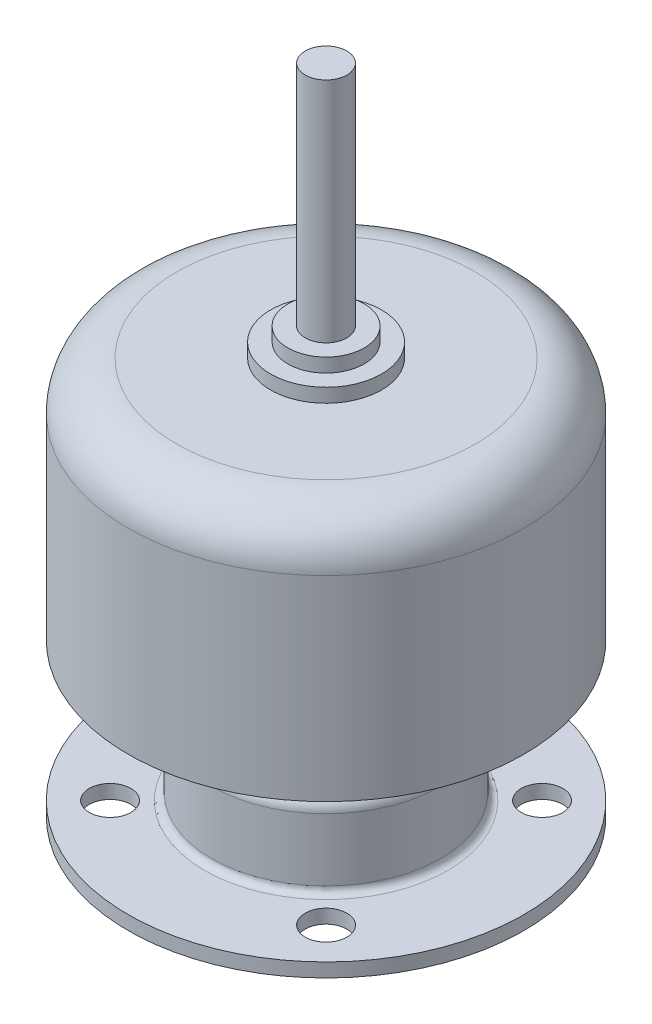
SolidWorks part; units mm, degrees
ref_plane "Alzado" through (0, 0, 0) normal (0, 0, 1) x (1, 0, 0)
ref_plane "Planta" through (0, 0, 0) normal (0, 1, 0) x (1, 0, 0)
ref_plane "Vista lateral" through (0, 0, 0) normal (1, 0, 0) x (0, 0, -1)
sketch "Croquis3" plane through (0, 0, 0) normal (0, 0, 1) x (1, 0, 0)
  line L0 (0, 0) -> (0, 47) construction
  line L1 (0, 0) -> (14.25, 0)
  line L2 (14.25, 0) -> (14.25, 1)
  line L3 (14.25, 1) -> (8.25, 1)
  line L4 (8.25, 1) -> (8.25, 7)
  line L5 (8.25, 7) -> (6.5, 7)
  line L6 (6.5, 7) -> (6.5, 11)
  line L8 (6.5, 11) -> (14.25, 11)
  line L9 (14.25, 11) -> (14.25, 28.6)
  line L11 (2.75, 29.6) -> (2.75, 30.6)
  line L12 (2.75, 30.6) -> (1.5, 30.6)
  line L15 (0, 0) -> (0, 47)
  line L19 (1.5, 30.6) -> (1.5, 47)
  line L20 (1.5, 47) -> (0, 47)
  line L21 (2.75, 29.6) -> (4, 29.6)
  line L22 (4, 29.6) -> (4, 28.6)
  line L23 (4, 28.6) -> (14.25, 28.6)
  point P19 (2.75, 30.1)
  dimension "D1" = 28.5
  dimension "D2" = 6.5
  dimension "D3" = 16.5
  dimension "D4" = 30.6
  dimension "D5" = 47
  dimension "D6" = 2.75
  dimension "D7" = 1
  dimension "D8" = 6
  dimension "D9" = 4
  dimension "D10" = 1
  dimension "D11" = 1
  dimension "D12" = 4
  dimension "D13" = 1.5
revolve "Revolución2" add sketch "Croquis3" angle 360 about L0
fillet "Redondeo4" radius 3.5 1 edges at (0, 28.6, -14.25)
sketch "Croquis7" plane through (0, 0, 0) normal (0, -1, 0) x (1, 0, 0)
  line L0 (0, 0) -> (7.7782, 7.7782) construction
  line L1 (0, 0) -> (11, 0)
  circle A0 centre (0, 0) radius 11
  circle A1 centre (7.7782, 7.7782) radius 1.5
  circle A2 centre (7.7782, -7.7782) radius 1.5
  circle A3 centre (-7.7782, -7.7782) radius 1.5
  circle A4 centre (-7.7782, 7.7782) radius 1.5
  point P15 (0, 0)
  dimension "D1" = 22
  dimension "D2" = 3
  dimension "D3" = 45
  dimension "D4" = 4
extrude "Cortar-Extruir1" cut sketch "Croquis7" against normal blind 10 contours A0 A3 | A0 A4 | A0 A1 | A0 A3 | A0 A4 | A2
fillet "Redondeo5" radius 1 1 edges at (0, 7, -8.25)
fillet "Redondeo6" radius 0.5 1 edges at (0, 1, -8.25)
